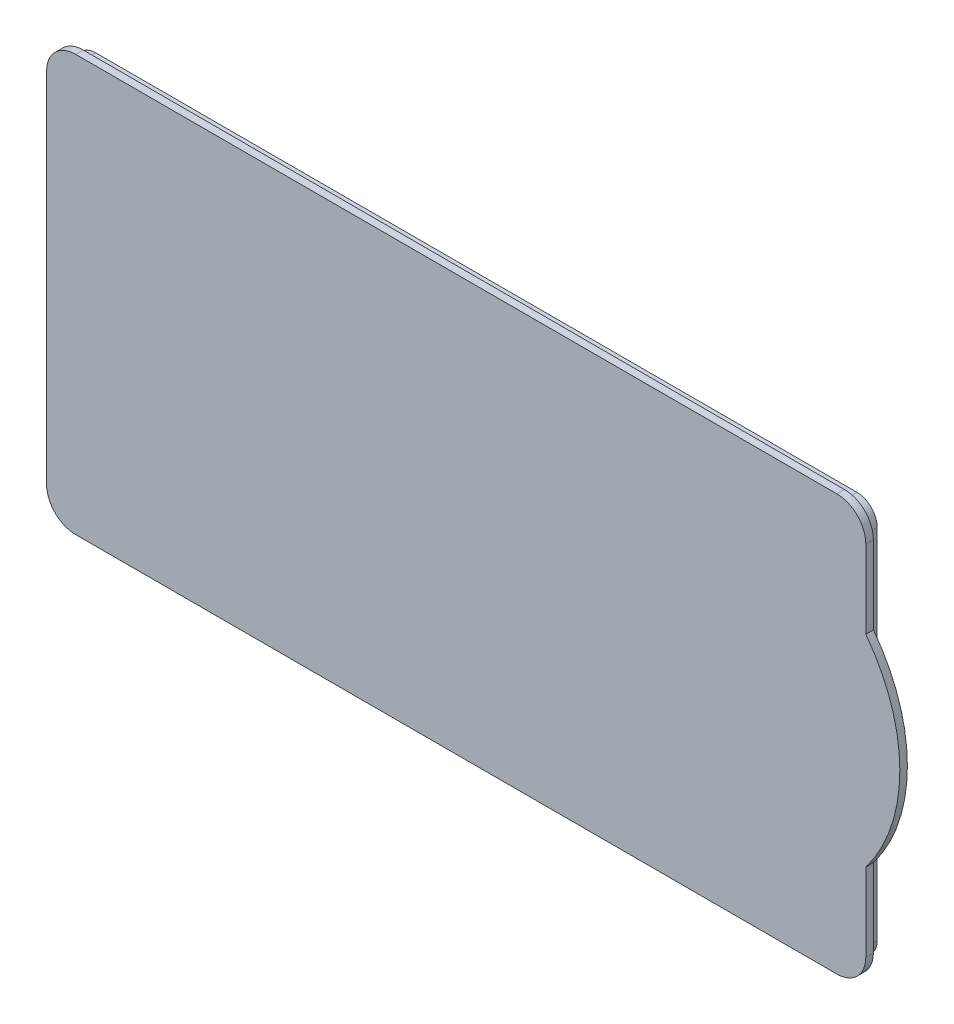
SolidWorks part; units mm, degrees
material "Стекло кварцевое прозрачное"
ref_plane "Спереди" through (0, 0, 0) normal (0, 0, 1) x (1, 0, 0)
ref_plane "Сверху" through (0, 0, 0) normal (0, 1, 0) x (1, 0, 0)
ref_plane "Справа" through (0, 0, 0) normal (1, 0, 0) x (0, 0, -1)
sketch "Sketch3" plane through (0, 0, 0) normal (0, 0, 1) x (1, 0, 0)
  line L4 (-161, 0) -> (161, 0) construction
  line L12 (0, 81) -> (0, -81) construction
  line L13 (-151, 81) -> (151, 81)
  line L14 (-161, 71) -> (-161, -71)
  line L15 (-151, -81) -> (151, -81)
  line L24 (161, 71) -> (161, -71)
  line L25 (-161, 81) -> (161, -81) construction
  line L26 (-161, -81) -> (161, 81) construction
  arc A12 (151, -81) -> (161, -71) centre (151, -71) ccw
  arc A13 (151, 81) -> (161, 71) centre (151, 71) cw
  arc A14 (-161, -71) -> (-151, -81) centre (-151, -71) ccw
  arc A15 (-151, 81) -> (-161, 71) centre (-151, 71) ccw
  point P0 (0, 0)
  dimension "D4" = 10
  dimension "D2" = 322
  dimension "D3" = 162
extrude "Boss-Extrude2" add sketch "Sketch3" against normal blind 3
sketch "Эскиз1" plane through (0, 0, -3) normal (0, 0, -1) x (-1, 0, 0)
  line L8 (-151, -79) -> (151, -79)
  line L9 (159, -71) -> (159, 71)
  line L10 (151, 79) -> (-151, 79)
  line L11 (-159, 71) -> (-159, -71)
  line L12 (-151, -79) -> (151, -79)
  line L13 (159, -71) -> (159, 71)
  line L14 (151, 79) -> (-151, 79)
  line L15 (-159, 71) -> (-159, -71)
  arc A8 (-159, -71) -> (-151, -79) centre (-151, -71) ccw
  arc A9 (151, -79) -> (159, -71) centre (151, -71) ccw
  arc A10 (159, 71) -> (151, 79) centre (151, 71) ccw
  arc A11 (-151, 79) -> (-159, 71) centre (-151, 71) ccw
  arc A12 (-159, -71) -> (-151, -79) centre (-151, -71) ccw
  arc A13 (151, -79) -> (159, -71) centre (151, -71) ccw
  arc A14 (159, 71) -> (151, 79) centre (151, 71) ccw
  arc A15 (-151, 79) -> (-159, 71) centre (-151, 71) ccw
  dimension "D1" = 2
extrude "Бобышка-Вытянуть1" add sketch "Эскиз1" along normal blind 5
sketch "Эскиз2" plane through (0, 0, 0) normal (0, 0, 1) x (1, 0, 0)
  line L0 (161, -71) -> (161, 71) construction
  line L5 (0, 105.4581) -> (0, -106.2128) construction
  line L6 (-173.7104, 0) -> (184.3927, 0) construction
  line L18 (162.5, 40) -> (162.5, 71)
  line L22 (162.5, -71) -> (162.5, 71)
  line L23 (151, 82.5) -> (-151, 82.5)
  line L24 (-162.5, 71) -> (-162.5, -71)
  line L25 (-151, -82.5) -> (151, -82.5)
  line L26 (162.5, -71) -> (162.5, -40)
  line L27 (151, 82.5) -> (-151, 82.5)
  line L28 (-162.5, 71) -> (-162.5, -71)
  line L29 (-151, -82.5) -> (151, -82.5)
  arc A7 (162.5, 40) -> (162.5, -40) centre (109.9907, 0) cw
  arc A16 (151, -82.5) -> (162.5, -71) centre (151, -71) ccw
  arc A17 (162.5, 71) -> (151, 82.5) centre (151, 71) ccw
  arc A18 (-151, 82.5) -> (-162.5, 71) centre (-151, 71) ccw
  arc A19 (-162.5, -71) -> (-151, -82.5) centre (-151, -71) ccw
  arc A20 (151, -82.5) -> (162.5, -71) centre (151, -71) ccw
  arc A21 (162.5, 71) -> (151, 82.5) centre (151, 71) ccw
  arc A22 (-151, 82.5) -> (-162.5, 71) centre (-151, 71) ccw
  arc A23 (-162.5, -71) -> (-151, -82.5) centre (-151, -71) ccw
  dimension "D1" = 15
  dimension "D2" = 80
  dimension "D3" = 1.5
extrude "Бобышка-Вытянуть2" add sketch "Эскиз2" against normal up to surface (3 mm away) up to face at (0, 0, -3)
equation "\"длина стекла\"=321 + 1"
equation "\"ширина стекла\"=161 + 1"
equation "\"D2@Sketch3\"=\"длина стекла\""
equation "\"D3@Sketch3\"=\"ширина стекла\""
